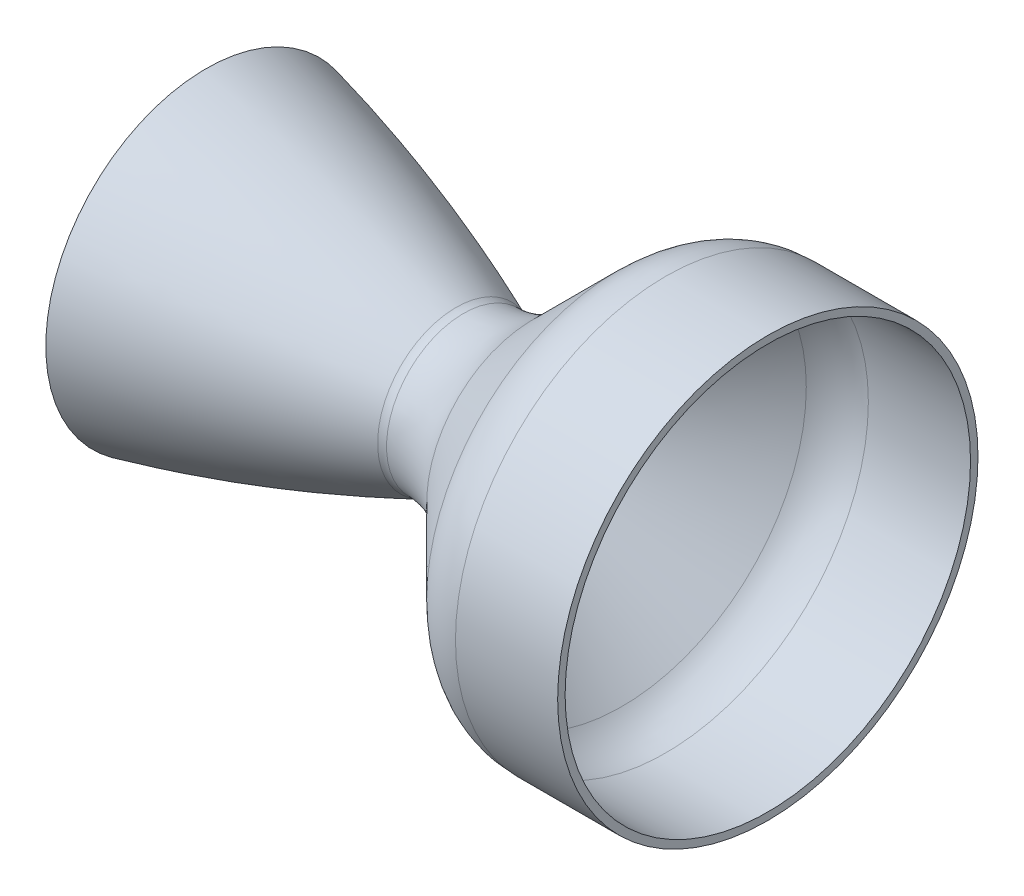
SolidWorks part; units mm, degrees
ref_plane "Front Plane" through (0, 0, 0) normal (0, 0, 1) x (1, 0, 0)
ref_plane "Top Plane" through (0, 0, 0) normal (0, 1, 0) x (1, 0, 0)
ref_plane "Right Plane" through (0, 0, 0) normal (1, 0, 0) x (0, 0, -1)
sketch "Sketch1" plane through (0, 0, 0) normal (0, 0, 1) x (1, 0, 0)
  line L0 (50.6746, 32.6533) -> (34.2162, 32.6533)
  line L1 (27.1452, 29.7244) -> (13.5414, 16.1206)
  line L3 (0, 0) -> (-234.9488, 0) construction
  line L8 (50.6746, 33.8533) -> (34.2162, 33.8533)
  line L12 (26.2966, 30.5729) -> (12.6928, 16.9691)
  line L14 (-40.0966, 24.6298) -> (-39.8247, 25.7986)
  line L16 (50.6746, 32.6533) -> (50.6746, 33.8533)
  arc A0 (34.2162, 32.6533) -> (27.1452, 29.7244) centre (34.2162, 22.6533) ccw
  arc A4 (34.2162, 33.8533) -> (26.2966, 30.5729) centre (34.2162, 22.6533) ccw
  arc A8 (12.6928, 16.9691) -> (1.034, 12.4126) centre (1.662, 28) cw construction
  arc A10 (0.7868, 11.2228) -> (0, 11.536) centre (8.1659, 30.9066) cw construction
  arc A11 (13.5414, 16.1206) -> (0.7868, 11.2228) centre (1.662, 28) cw construction
  arc A12 (13.5414, 16.1206) -> (1.662, 11.2) centre (1.662, 28) cw
  arc A13 (1.662, 11.2) -> (0, 11.536) centre (1.662, 15.4784) cw
  arc A14 (12.6928, 16.9691) -> (1.662, 12.4) centre (1.662, 28) cw
  arc A15 (0.4661, 12.6418) -> (1.662, 12.4) centre (1.662, 15.4784) ccw
  arc A16 (1.034, 12.4126) -> (0.4661, 12.6418) centre (8.1659, 30.9066) cw construction
  spline S0 degree 2 poles (0, 11.536) (-19.9352, 19.9399) (-40.0966, 24.6298) knots 0 0 0 1 1 1 construction
  spline S1 degree 1 poles (0.4661, 12.6418) (-39.8247, 25.7986) knots 0 0 1 1 construction
  spline S2 degree 2 poles (0, 11.536) (-19.9352, 19.9399) (-40.0966, 24.6298) knots 0 0 0 1 1 1
  spline S3 degree 2 poles (0.4661, 12.6418) (-19.5592, 21.0841) (-39.8247, 25.7986) knots 0 0 0 1 1 1
  dimension "D1" = 10
  dimension "D4" = 16.8
  dimension "D5" = 4.2784
  dimension "D14" = 32.6533
  dimension "D16" = 23.5294
  dimension "D2" = 11.2
  dimension "D6" = 45
  dimension "D7" = 24.6298
  dimension "D3" = 1.2
revolve "Revolve1" add sketch "Sketch1" angle 360 about L3
equation "\"theta_t\"= 36.9009 - ( 426.271 / ( \"Aet\" + 7.00037 ) ) + ( 10026.8 / ( \"Aet\" + 7.00037 ) ^ 2 ) - ( 175410 / ( \"Aet\" + 7.00037 ) ^ 3 ) + ( ( 1.6742 * ( 10 ^ 6 ) ) / ( \"Aet\" + 7.00037 ) ^ 4 ) - ( ( 6.7643 * ( 10 ^ 6 ) ) / ( \"Aet\" + 7.00037 ) ^ 5 )'Do NOT change!"
equation "\"rt\"= 11.2'Desired throat radius here"
equation "\"re\"= sqr ( \"rt\" ^ 2 * \"Aet\" )'Do NOT change!"
equation "\"Aet\"= 4.836'Desired exit area ratio here"
equation "\"L\"= 0.8 * ( ( \"re\" / tan ( 15 ) ) - ( \"rt\" / tan ( 15 ) ) )'Do NOT change!"
equation "\"lc\"= ( \"l*\" / \"cr\" )'Do NOT change!"
equation "\"b\"= tan ( \"theta_t\" )'Do NOT change!"
equation "\"a\"= ( \"re\" - \"b\" * \"L\" - \"c\" ) / \"L\" ^ 2'Do NOT change!"
equation "\"c\"= \"rt\" * ( 1.382 - 0.382 * cos ( \"theta_t\" ) )'Do NOT change!"
equation "\"cr\"= 8.5'Desired contraction ratio here"
equation "\"rc\"= sqr ( \"cr\" * ( \"rt\" ^ 2 ) )'Do NOT change!"
equation "\"D14@Sketch1\"=\"rc\""
equation "\"l*\"= 200'Desired specific length here"
equation "\"D16@Sketch1\"=\"lc\""
equation "\"th\"= 1.2'Desired wall thickness here"
equation "\"theta_cr\"= 45deg'Desired contraction angle here"
equation "\"theta_e\"= 5.48 + ( 134.316 / ( \"Aet\" + 1.49269 ) ) - ( 1742.02 / ( \"Aet\" + 1.49269 ) ^ 2 ) + ( 13091 / ( \"Aet\" + 1.49269 ) ^ 3 ) - ( 41929.9 / ( \"Aet\" + 1.49269 ) ^ 4 ) + ( 44445.1 / ( \"Aet\" + 1.49269 ) ^ 5 )'Do NOT change!"
equation "\"Nx\"= 0'Do NOT change!"
equation "\"Ny\"= \"c\"'Do NOT change!"
equation "\"Qx\"= ( \"re\" - ( tan ( \"theta_e\" ) * \"L\" ) - \"c\" ) / ( tan ( \"theta_t\" ) - tan ( \"theta_e\" ) )'Do NOT change!"
equation "\"Qy\"= tan ( \"theta_t\" ) * \"Qx\" + \"c\"'Do NOT change!"
equation "\"Ex\"= \"L\"'Do NOT change!"
equation "\"Ey\"= \"re\"'Do NOT change!"
equation "\"D3@Sketch1\"=\"th\""
equation "\"D2@Sketch1\"=\"rt\""
equation "\"D4@Sketch1\"=\"rt\"*1.5"
equation "\"D5@Sketch1\"=\"rt\"*0.382"
equation "\"D6@Sketch1\"=\"theta_cr\""
equation "\"D7@Sketch1\"=\"re\""
